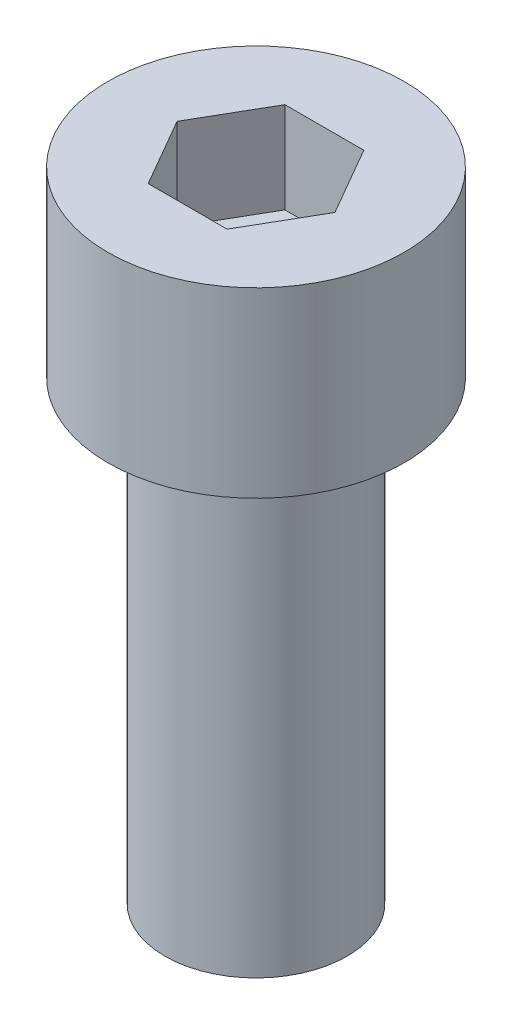
SolidWorks part; units mm, degrees
material "AISI 304"
ref_plane "Front Plane" through (0, 0, 0) normal (0, 0, 1) x (1, 0, 0)
ref_plane "Top Plane" through (0, 0, 0) normal (0, 1, 0) x (1, 0, 0)
ref_plane "Right Plane" through (0, 0, 0) normal (1, 0, 0) x (0, 0, -1)
sketch "Sketch1" plane through (0, 0, 0) normal (0, 0, 1) x (1, 0, 0)
  line L0 (0, 61.6916) -> (0, -59.3578) construction
  line L1 (0, -20) -> (4, -20)
  line L2 (4, -20) -> (4, 0)
  line L3 (4, 0) -> (6.5, 0)
  line L4 (6.5, 0) -> (6.5, 8)
  line L5 (6.5, 8) -> (0, 8)
  line L6 (0, 8) -> (0, -20)
  dimension "D1" = 20
  dimension "D2" = 13
  dimension "D3" = 8
  dimension "D4" = 8
revolve "Revolve1" add sketch "Sketch1" angle 360 about L0
sketch "Sketch2" plane through (0, 8, 0) normal (0, 1, 0) x (-1, 0, 0)
  line L1 (-1.7321, -3) -> (1.7321, -3)
  line L2 (1.7321, -3) -> (3.4641, 0)
  line L3 (3.4641, 0) -> (1.7321, 3)
  line L4 (1.7321, 3) -> (-1.7321, 3)
  line L5 (-1.7321, 3) -> (-3.4641, 0)
  line L6 (-3.4641, 0) -> (-1.7321, -3)
  circle A0 centre (0, 0) radius 3 construction
  dimension "D1" = 6
extrude "Cut-Extrude1" cut sketch "Sketch2" against normal blind 4
